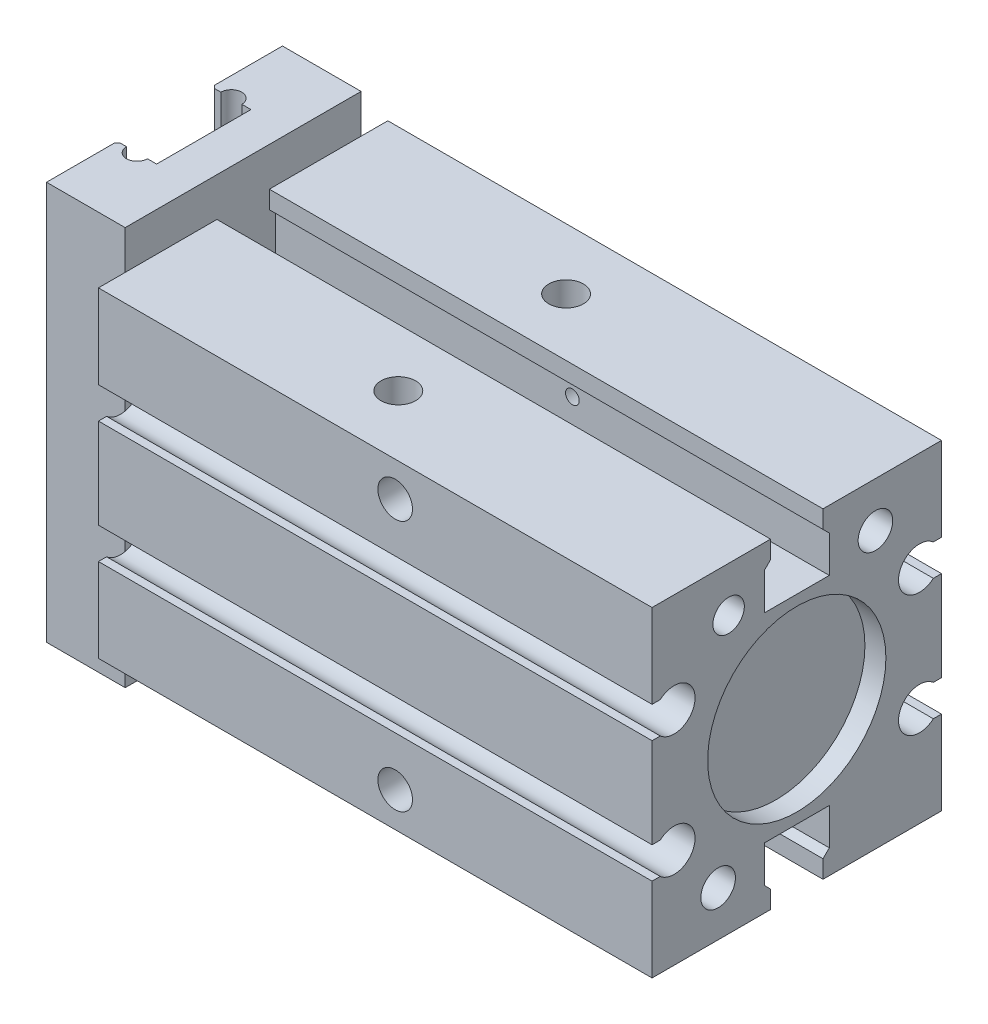
SolidWorks part; units mm, degrees
ref_plane "Front Plane" through (0, 0, 0) normal (0, 0, 1) x (1, 0, 0)
ref_plane "Top Plane" through (0, 0, 0) normal (0, 1, 0) x (1, 0, 0)
ref_plane "Right Plane" through (0, 0, 0) normal (1, 0, 0) x (0, 0, -1)
sketch "Sketch1" plane through (0, 0, 0) normal (0, 0, 1) x (1, 0, 0)
  line L1 (26.4, -15.3) -> (-26.4, -15.3)
  line L2 (26.4, -15.3) -> (26.4, 15.3)
  line L3 (26.4, 15.3) -> (-26.4, 15.3)
  line L4 (-26.4, -15.3) -> (-26.4, 15.3)
  line L5 (26.4, -15.3) -> (-26.4, 15.3) construction
  line L6 (26.4, 15.3) -> (-26.4, -15.3) construction
  point P0 (0, 0)
  dimension "D1" = 52.8
  dimension "D2" = 30.6
extrude "EXT BODY" add sketch "Sketch1" along normal mid plane 27.6
sketch "Sketch2" plane through (26.4, 0, 0) normal (1, 0, 0) x (0, 0, -1)
  line L0 (13.8, 0) -> (-13.8, 0) construction
  line L1 (-13.8, -15.3) -> (-13.8, 15.3) construction
  line L2 (0, -15.3) -> (0, 15.3) construction
  line L3 (-13.8, 15.3) -> (13.8, 15.3) construction
  line L4 (2.5, 15.3) -> (-2.5, 15.3)
  line L5 (-2.5, 15.3) -> (-2.5, 13.6)
  line L6 (-2.5, 13.6) -> (-3.1, 13)
  line L7 (-3.1, 13) -> (-3.1, 9.5)
  line L8 (-3.1, 9.5) -> (3.1, 9.5)
  line L9 (-11.7, 5.8) -> (-13.8, 5.8) construction
  line L10 (-13.0229, 7.3) -> (-13.8, 7.3)
  line L11 (-13.0229, 4.3) -> (-13.8, 4.3)
  line L12 (-13.8, 7.3) -> (-13.8, 4.3)
  line L13 (-11.7, -5.8) -> (-13.8, -5.8) construction
  line L14 (-13.8, -7.3) -> (-13.8, -4.3)
  line L15 (-13.0229, -4.3) -> (-13.8, -4.3)
  line L16 (-13.0229, -7.3) -> (-13.8, -7.3)
  line L17 (-3.1, -9.5) -> (3.1, -9.5)
  line L18 (-3.1, -13) -> (-3.1, -9.5)
  line L19 (-2.5, -13.6) -> (-3.1, -13)
  line L20 (-2.5, -15.3) -> (-2.5, -13.6)
  line L21 (2.5, -15.3) -> (-2.5, -15.3)
  line L22 (11.7, -5.8) -> (13.8, -5.8) construction
  line L23 (11.7, 5.8) -> (13.8, 5.8) construction
  line L24 (2.5, -15.3) -> (2.5, -13.6)
  line L25 (2.5, -13.6) -> (3.1, -13)
  line L26 (3.1, -13) -> (3.1, -9.5)
  line L27 (13.0229, -7.3) -> (13.8, -7.3)
  line L28 (13.0229, -4.3) -> (13.8, -4.3)
  line L29 (13.8, -7.3) -> (13.8, -4.3)
  line L30 (13.8, 7.3) -> (13.8, 4.3)
  line L31 (13.0229, 4.3) -> (13.8, 4.3)
  line L32 (13.0229, 7.3) -> (13.8, 7.3)
  line L33 (3.1, 13) -> (3.1, 9.5)
  line L34 (2.5, 13.6) -> (3.1, 13)
  line L35 (2.5, 15.3) -> (2.5, 13.6)
  arc A0 (-13.0229, 4.3) -> (-13.0229, 7.3) centre (-11.7, 5.8) ccw
  arc A1 (-13.0229, -4.3) -> (-13.0229, -7.3) centre (-11.7, -5.8) cw
  arc A2 (13.0229, -4.3) -> (13.0229, -7.3) centre (11.7, -5.8) ccw
  arc A3 (13.0229, 4.3) -> (13.0229, 7.3) centre (11.7, 5.8) cw
  point P36 (0, 0)
  point P44 (0, -9.5)
  point P49 (0, 9.5)
  dimension "D6" = 4
  dimension "D1" = 3.1
  dimension "D2" = 2.5
  dimension "D3" = 5.8
  dimension "D4" = 3.5
  dimension "D5" = 135
  dimension "D7" = 5.8
  dimension "D8" = 2.1
  dimension "D9" = 1.5
extrude "AUTO SWITCH MOUNTING" cut sketch "Sketch2" against normal through all
sketch "Sketch3" plane through (26.4, 0, 0) normal (1, 0, 0) x (0, 0, -1)
  circle A0 centre (0, 0) radius 8.5
  dimension "D1" = 17
extrude "CYL BORE" cut sketch "Sketch3" against normal blind 2
sketch "Sketch4" plane through (26.4, 0, 0) normal (1, 0, 0) x (0, 0, -1)
  line L0 (13.8, 0) -> (-13.8, 0) construction
  line L1 (13.8, -4.3) -> (13.8, 4.3) construction
  line L2 (-13.8, -4.3) -> (-13.8, 4.3) construction
  line L3 (0, 0) -> (0, 9.5) construction
  line L4 (-3.1, 9.5) -> (3.1, 9.5) construction
  point P11 (-6.5, 11)
  point P12 (7.5, 11)
  point P13 (-7.5, -11)
  dimension "D1" = 6.5
  dimension "D2" = 11
  dimension "D3" = 7.5
  dimension "D4" = 7.5
  dimension "D5" = 11
hole_wizard "M4x0.7 Tapped Hole1" positions "Sketch6" profile "Sketch5" tap size "M4x0.7" standard "ANSI Metric"
sketch "Sketch6" plane through (26.4, 0, 0) normal (1, 0, 0) x (0, 0, -1)
  point P0 (-7.5, -11)
  point P3 (7.5, 11)
sketch "Sketch5" plane through (26.4, -11, 7.5) normal (0, 1, 0) x (0, 0, -1)
  line L0 (0, 0) -> (0, 11.0914)
  line L1 (0, 11.0914) -> (1.65, 10.1)
  line L2 (1.65, 10.1) -> (1.65, 0)
  line L5 (1.65, 0) -> (0, 0)
  line L10 (0, 11.0914) -> (-1.65, 10.1) construction
  line L11 (0, -6.35) -> (0, 107.95) construction
  dimension "Tap Drill Dia." = 3.3
  dimension "Tap Drill Depth" = 10.1
  dimension "Drill Angle" = 118
cosmetic thread "Hole Thread1" parameters "D1"=8, "D2"=4
cosmetic thread "Hole Thread2" parameters "D1"=8, "D2"=4
hole_wizard "Ø3.0 (3) Diameter Hole1" positions "Sketch8" profile "Sketch7" hole size "Ø3.0" standard "ANSI Metric"
sketch "Sketch8" plane through (26.4, 0, 0) normal (1, 0, 0) x (0, 0, -1)
  point P0 (-6.5, 11)
sketch "Sketch7" plane through (26.4, 11, 6.5) normal (0, 1, 0) x (0, 0, -1)
  line L0 (0, 0) -> (0, 3.9013)
  line L1 (0, 3.9013) -> (1.5, 3)
  line L2 (1.5, 3) -> (1.5, 0)
  line L5 (1.5, 0) -> (0, 0)
  line L10 (0, 3.9013) -> (-1.5, 3) construction
  line L11 (0, -6.35) -> (0, 107.95) construction
  dimension "Hole Dia." = 3
  dimension "Hole Depth" = 3
  dimension "Drill Angle" = 118
sketch "Sketch9" plane through (0, 0, 13.8) normal (0, 0, 1) x (1, 0, 0)
  line L0 (1.9, 15.3) -> (1.9, -15.3) construction
  line L1 (26.4, 15.3) -> (-26.4, 15.3) construction
  line L2 (-26.4, -15.3) -> (26.4, -15.3) construction
  line L3 (26.4, 0) -> (0, 0) construction
  line L4 (26.4, -4.3) -> (26.4, 4.3) construction
  point P11 (1.9, 12)
  point P12 (1.9, -12)
  dimension "D1" = 24.5
  dimension "D2" = 12
hole_wizard "M4x0.7 Tapped Hole2" positions "Sketch11" profile "Sketch10" tap size "M4x0.7" standard "ANSI Metric"
sketch "Sketch11" plane through (0, 0, 13.8) normal (0, 0, 1) x (1, 0, 0)
  point P0 (1.9, 12)
  point P3 (1.9, -12)
cosmetic thread "Hole Thread3" parameters "D1"=8, "D2"=4
cosmetic thread "Hole Thread4" parameters "D1"=8, "D2"=4
sketch "Sketch10" plane through (1.9, 12, 13.8) normal (1, 0, 0) x (0, -1, 0)
  line L0 (0, 0) -> (0, 11.0914)
  line L1 (0, 11.0914) -> (1.65, 10.1)
  line L2 (1.65, 10.1) -> (1.65, 0)
  line L5 (1.65, 0) -> (0, 0)
  line L10 (0, 11.0914) -> (-1.65, 10.1) construction
  line L11 (0, -6.35) -> (0, 107.95) construction
  dimension "Tap Drill Dia." = 3.3
  dimension "Tap Drill Depth" = 10.1
  dimension "Drill Angle" = 118
hole_wizard "M4x0.7 Tapped Hole3" positions "Sketch14" profile "Sketch12" tap size "M4x0.7" standard "ANSI Metric"
sketch "Sketch14" plane through (0, 0, -13.8) normal (0, 0, -1) x (-1, 0, 0)
  point P0 (-1.9, 12)
  point P3 (-1.9, -12)
sketch "Sketch12" plane through (1.9, 12, -13.8) normal (1, 0, 0) x (0, 1, 0)
  line L0 (0, 0) -> (0, 11.0914)
  line L1 (0, 11.0914) -> (1.65, 10.1)
  line L2 (1.65, 10.1) -> (1.65, 0)
  line L5 (1.65, 0) -> (0, 0)
  line L10 (0, 11.0914) -> (-1.65, 10.1) construction
  line L11 (0, -6.35) -> (0, 107.95) construction
  dimension "Tap Drill Dia." = 3.3
  dimension "Tap Drill Depth" = 10.1
  dimension "Drill Angle" = 118
cosmetic thread "Hole Thread5" parameters "D1"=8, "D2"=4
cosmetic thread "Hole Thread6" parameters "D1"=8, "D2"=4
sketch "Sketch15" plane through (0, 15.3, 0) normal (0, 1, 0) x (1, 0, 0)
  line L0 (-3.6, 13.8) -> (-3.6, -13.8) construction
  line L1 (26.4, 13.8) -> (-26.4, 13.8) construction
  line L2 (26.4, -13.8) -> (-26.4, -13.8) construction
  line L3 (0, 0) -> (-26.4, 0) construction
  line L4 (-26.4, -3.1) -> (-26.4, 3.1) construction
  line L5 (26.4, 2.5) -> (26.4, 13.8) construction
  point P13 (-3.6, 8)
  point P14 (-3.6, -8)
  dimension "D1" = 30
  dimension "D2" = 8
hole_wizard "M4x0.7 Tapped Hole4" positions "Sketch17" profile "Sketch16" tap size "M4x0.7" standard "ANSI Metric"
sketch "Sketch17" plane through (0, 15.3, 0) normal (0, 1, 0) x (1, 0, 0)
  point P0 (-3.6, 8)
  point P3 (-3.6, -8)
sketch "Sketch16" plane through (-3.6, 15.3, -8) normal (1, 0, 0) x (0, 0, 1)
  line L0 (0, 0) -> (0, 7.5914)
  line L1 (0, 7.5914) -> (1.65, 6.6)
  line L2 (1.65, 6.6) -> (1.65, 0)
  line L5 (1.65, 0) -> (0, 0)
  line L10 (0, 7.5914) -> (-1.65, 6.6) construction
  line L11 (0, -6.35) -> (0, 107.95) construction
  dimension "Tap Drill Dia." = 3.3
  dimension "Tap Drill Depth" = 6.6
  dimension "Drill Angle" = 118
cosmetic thread "Hole Thread7" parameters "D1"=4.5, "D2"=4
cosmetic thread "Hole Thread8" parameters "D1"=4.5, "D2"=4
sketch "Sketch18" plane through (0, -15.3, 0) normal (0, -1, 0) x (1, 0, 0)
  line L0 (26.4, 0) -> (0, 0) construction
  line L1 (26.4, -3.1) -> (26.4, 3.1) construction
  line L2 (18.9, 0) -> (18.9, -13.8) construction
  line L3 (-26.4, -13.8) -> (26.4, -13.8) construction
  line L4 (7.4, 0) -> (7.4, 13.8) construction
  line L5 (-26.4, 13.8) -> (26.4, 13.8) construction
  line L6 (26.4, 13.8) -> (26.4, 2.5) construction
  line L7 (26.4, -2.5) -> (26.4, -13.8) construction
  point P17 (7.4, 7.5)
  point P18 (18.9, -7.5)
  dimension "D1" = 19
  dimension "D2" = 7.5
  dimension "D3" = 7.5
  dimension "D4" = 7.5
hole_wizard "M5x0.8 Tapped Hole1" positions "Sketch20" profile "Sketch19" tap size "M5x0.8" standard "ANSI Metric"
sketch "Sketch20" plane through (0, -15.3, 0) normal (0, -1, 0) x (-1, 0, 0)
  point P0 (-7.4, -7.5)
  point P3 (-18.9, 7.5)
sketch "Sketch19" plane through (7.4, -15.3, 7.5) normal (1, 0, 0) x (0, 0, -1)
  line L0 (0, 0) -> (0, 7.2618)
  line L1 (0, 7.2618) -> (2.1, 6)
  line L2 (2.1, 6) -> (2.1, 0)
  line L5 (2.1, 0) -> (0, 0)
  line L10 (0, 7.2618) -> (-2.1, 6) construction
  line L11 (0, -6.35) -> (0, 107.95) construction
  dimension "Tap Drill Dia." = 4.2
  dimension "Tap Drill Depth" = 6
  dimension "Drill Angle" = 118
cosmetic thread "Hole Thread9" parameters "D1"=4, "D2"=5
cosmetic thread "Hole Thread10" parameters "D1"=4, "D2"=5
sketch "Sketch21" plane through (0, 0, 0) normal (0, 1, 0) x (1, 0, 0)
  line L0 (0, 0) -> (-33.9, 0) construction
  line L1 (-30.15, -4.5) -> (-33.9, -4.5) construction
  line L2 (-26.4, -13.8) -> (-26.4, -2.5) construction
  line L3 (-33.9, 4.5) -> (-33.9, 11.25)
  line L4 (-33.9, 11.25) -> (-26.4, 11.25)
  line L5 (-26.4, 2.5) -> (-26.4, 13.8) construction
  line L6 (-26.4, 11.25) -> (-26.4, -11.25)
  line L7 (-26.4, -3.1) -> (-26.4, 3.1) construction
  line L8 (-33.9, 4.5) -> (-33.025, 4.5)
  line L9 (-30.15, 4.5) -> (-30.15, -4.5)
  line L10 (-31.025, 4.5) -> (-30.15, 4.5)
  line L11 (-30.15, 4.5) -> (-33.9, 4.5) construction
  line L12 (-31.025, -4.5) -> (-30.15, -4.5)
  line L13 (-33.9, -4.5) -> (-33.025, -4.5)
  line L14 (-33.9, -11.25) -> (-26.4, -11.25)
  line L15 (-33.9, -4.5) -> (-33.9, -11.25)
  arc A0 (-31.025, 4.5) -> (-33.025, 4.5) centre (-32.025, 4.5) ccw
  arc A1 (-31.025, -4.5) -> (-33.025, -4.5) centre (-32.025, -4.5) cw
  point P16 (-32.025, 4.5)
  point P24 (-30.15, 0)
  point P25 (-26.4, 0)
  dimension "D4" = 2
  dimension "D1" = 7.5
  dimension "D2" = 11.25
  dimension "D3" = 4.5
  dimension "D5" = 3.75
  dimension "D6" = 7.5
extrude "Boss-Extrude2" add sketch "Sketch21" along normal mid plane 38
chamfer "Chamfer1" distance 0.25 angle 45 2 edges at (-33.9, 0, 4.5) (-33.9, 0, -4.5)
ref_plane "Plane1" through (0, 0, 0) normal (0, 1, 0) x (1, 0, 0)
